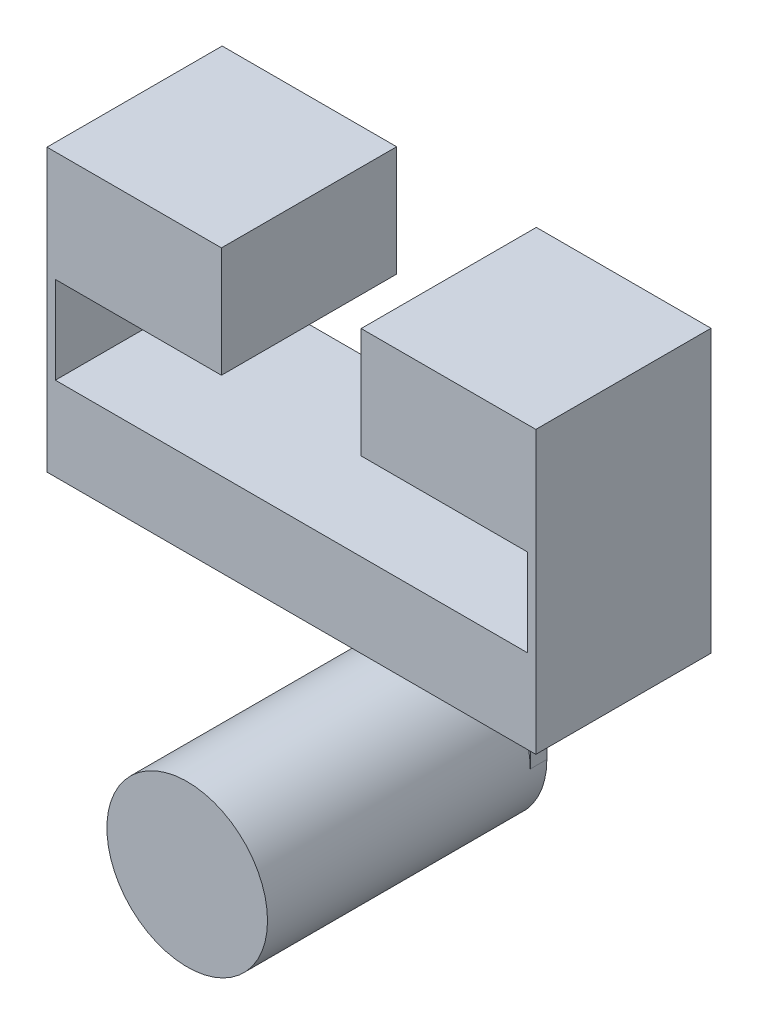
SolidWorks part; units mm, degrees
ref_plane "Front Plane" through (0, 0, 0) normal (0, 0, 1) x (1, 0, 0)
ref_plane "Top Plane" through (0, 0, 0) normal (0, 1, 0) x (1, 0, 0)
ref_plane "Right Plane" through (0, 0, 0) normal (1, 0, 0) x (0, 0, -1)
sketch "Sketch1" plane through (0, 0, 0) normal (0, 0, 1) x (1, 0, 0)
  circle A0 centre (0, 0) radius 14.605
extrude "Boss-Extrude1" add sketch "Sketch1" against normal blind 50.8 contours A0
sketch "Sketch2" plane through (0, 0, -50.8) normal (0, 0, -1) x (-1, 0, 0)
  line L1 (-14.605, 0) -> (14.605, 0)
  line L2 (-14.605, 0) -> (-14.605, 31.6499)
  line L3 (-14.605, 31.6499) -> (14.605, 31.6499)
  line L4 (14.605, 0) -> (14.605, 31.6499)
  circle A0 centre (0, 0) radius 14.605 construction
extrude "Boss-Extrude3" add sketch "Sketch2" against normal blind 3.0201
sketch "Sketch3" plane through (0, 31.6499, 0) normal (0, 1, 0) x (1, 0, 0)
  line L0 (-14.605, 50.8) -> (-44.4425, 50.8)
  line L1 (-44.4425, 50.8) -> (-44.4425, 18.942)
  line L2 (-44.4425, 18.942) -> (44.4575, 18.942)
  line L3 (44.4575, 18.942) -> (44.4575, 50.8)
  line L4 (44.4575, 50.8) -> (-14.605, 50.8)
extrude "Boss-Extrude4" add sketch "Sketch3" along normal blind 15.24
sketch "Sketch4" plane through (0, 46.8899, 0) normal (0, 1, 0) x (1, 0, 0)
  line L0 (44.4575, 50.8) -> (42.9335, 50.8)
  line L1 (44.4575, 50.8) -> (-44.4425, 50.8) construction
  line L2 (42.9335, 50.8) -> (42.9335, 18.942)
  line L3 (-44.4425, 18.942) -> (44.4575, 18.942) construction
  line L4 (42.9335, 18.942) -> (44.4575, 18.942)
  line L5 (44.4575, 18.942) -> (44.4575, 50.8)
  line L6 (-44.4425, 50.8) -> (-44.4425, 18.942)
  line L7 (-44.4425, 18.942) -> (-42.9185, 18.942)
  line L8 (-42.9185, 18.942) -> (-42.9185, 50.8)
  line L9 (-42.9185, 50.8) -> (-44.4425, 50.8)
extrude "Boss-Extrude6" add sketch "Sketch4" along normal blind 15.875
sketch "Sketch5" plane through (0, 62.7649, 0) normal (0, 1, 0) x (1, 0, 0)
  line L0 (-44.4425, 50.8) -> (-12.7159, 50.8)
  line L1 (42.9335, 50.8) -> (-42.9185, 50.8) construction
  line L2 (-12.7159, 50.8) -> (-12.7159, 18.942)
  line L3 (-42.9185, 18.942) -> (42.9335, 18.942) construction
  line L4 (-12.7159, 18.942) -> (-44.4425, 18.942)
  line L5 (-44.4425, 18.942) -> (-44.4425, 50.8)
  line L6 (44.4575, 50.8) -> (12.6898, 50.8)
  line L7 (12.6898, 50.8) -> (12.6898, 18.942)
  line L8 (12.6898, 18.942) -> (44.4575, 18.942)
  line L9 (44.4575, 18.942) -> (44.4575, 50.8)
extrude "Boss-Extrude7" add sketch "Sketch5" along normal blind 20.066
